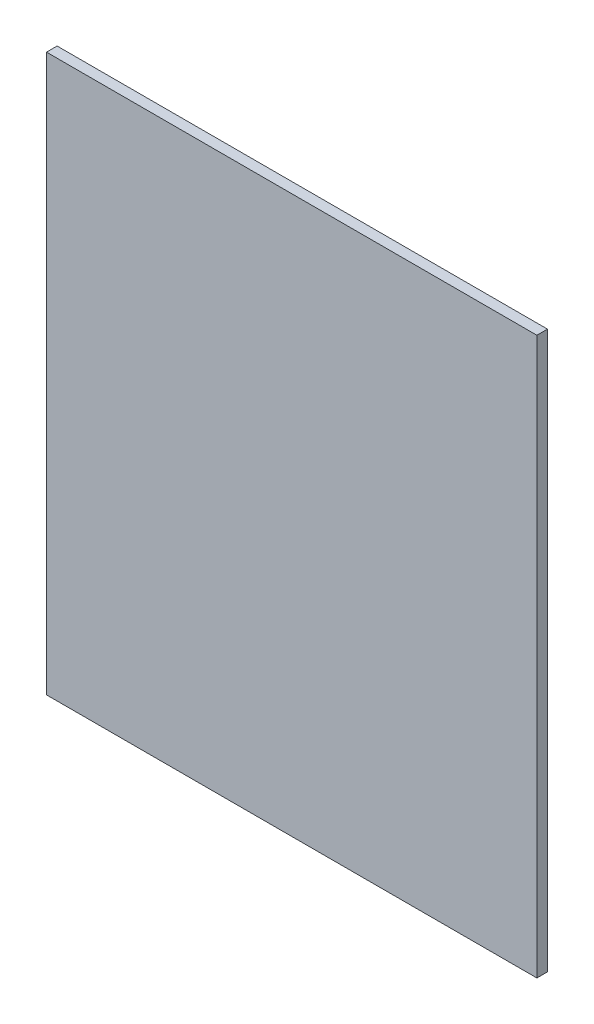
SolidWorks part; units mm, degrees
ref_plane "Front Plane" through (0, 0, 0) normal (0, 0, 1) x (1, 0, 0)
ref_plane "Top Plane" through (0, 0, 0) normal (0, 1, 0) x (1, 0, 0)
ref_plane "Right Plane" through (0, 0, 0) normal (1, 0, 0) x (0, 0, -1)
sketch "Sketch1" plane through (0, 0, 0) normal (0, 0, 1) x (1, 0, 0)
  line L1 (-46.25, 52.5) -> (46.25, 52.5)
  line L2 (-46.25, 52.5) -> (-46.25, -52.5)
  line L3 (-46.25, -52.5) -> (46.25, -52.5)
  line L4 (46.25, 52.5) -> (46.25, -52.5)
  line L5 (-46.25, 52.5) -> (46.25, -52.5) construction
  line L6 (-46.25, -52.5) -> (46.25, 52.5) construction
  point P0 (0, 0)
  dimension "D1" = 105
  dimension "D2" = 92.5
extrude "Boss-Extrude1" add sketch "Sketch1" along normal blind 2
